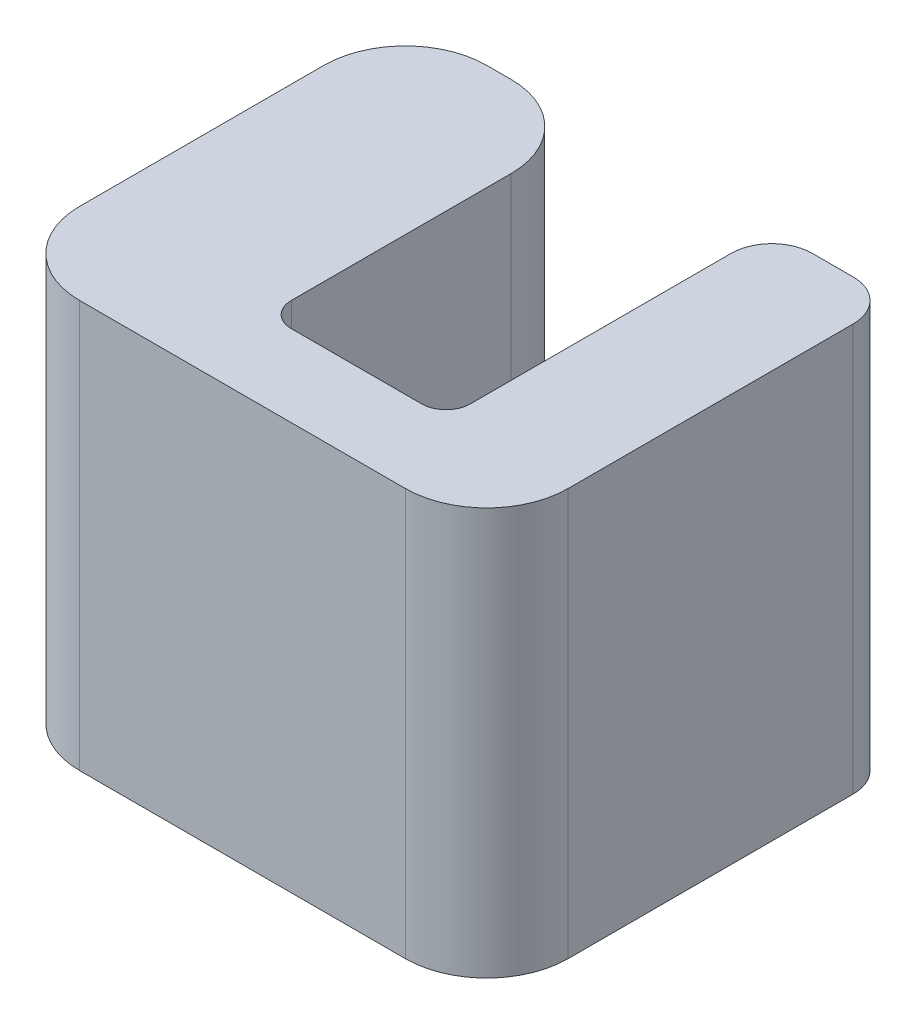
SolidWorks part; units mm, degrees
ref_plane "Plano frontal" through (0, 0, 0) normal (0, 0, 1) x (1, 0, 0)
ref_plane "Plano superior" through (0, 0, 0) normal (0, 1, 0) x (1, 0, 0)
ref_plane "Plano direito" through (0, 0, 0) normal (1, 0, 0) x (0, 0, -1)
sketch "Esboço1" plane through (0, 0, 0) normal (0, 1, 0) x (1, 0, 0)
  line L1 (-3, -2.5) -> (3, -2.5)
  line L2 (-3, -2.5) -> (-3, 2.5)
  line L3 (-3, 2.5) -> (3, 2.5)
  line L4 (3, -2.5) -> (3, 2.5)
  line L5 (-3, -2.5) -> (3, 2.5) construction
  line L6 (-3, 2.5) -> (3, -2.5) construction
  point P0 (0, 0)
  dimension "D1" = 6
  dimension "D2" = 5
extrude "Ressalto-extrusão1" add sketch "Esboço1" along normal blind 5
sketch "Esboço3" plane through (0, 5, 0) normal (0, 1, 0) x (1, 0, 0)
  line L0 (3, 2.5) -> (-3, 2.5) construction
  line L1 (-0.7, 2.5) -> (1.5, 2.5)
  line L2 (-0.7, 2.5) -> (-0.7, -1.5)
  line L3 (-0.7, -1.5) -> (1.5, -1.5)
  line L4 (1.5, 2.5) -> (1.5, -1.5)
  line L5 (3, -2.5) -> (3, 2.5) construction
  dimension "D1" = 4
  dimension "D2" = 2.2
  dimension "D3" = 1.5
extrude "Corte-extrusão1" cut sketch "Esboço3" against normal blind 5
fillet "Filete1" radius 1 1 edges at (3, 2.5, 2.5)
fillet "Filete2" radius 1 1 edges at (-3, 2.5, 2.5)
fillet "Filete3" radius 1 1 edges at (-3, 2.5, -2.5)
fillet "Filete4" radius 1 1 edges at (-0.7, 2.5, -2.5)
fillet "Filete5" radius 0.5 1 edges at (1.5, 2.5, -2.5)
fillet "Filete6" radius 0.5 1 edges at (3, 2.5, -2.5)
fillet "Filete7" radius 0.3 1 edges at (1.5, 2.5, 1.5)
fillet "Filete8" radius 0.3 1 edges at (-0.7, 2.5, 1.5)
